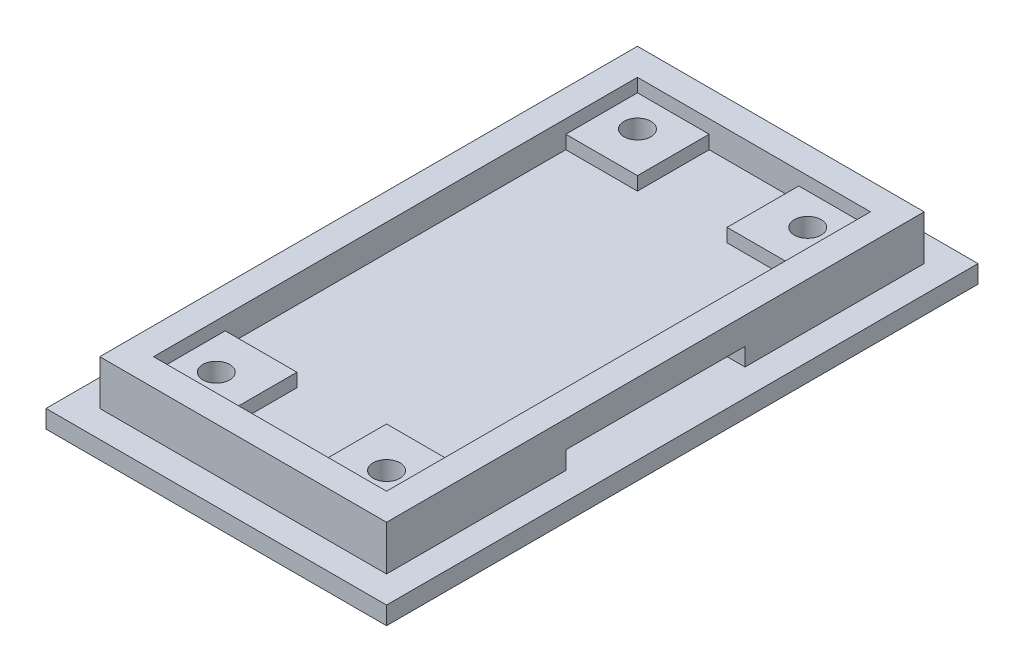
SolidWorks part; units mm, degrees
ref_plane "Front Plane" through (0, 0, 0) normal (0, 0, 1) x (1, 0, 0)
ref_plane "Top Plane" through (0, 0, 0) normal (0, 1, 0) x (1, 0, 0)
ref_plane "Right Plane" through (0, 0, 0) normal (1, 0, 0) x (0, 0, -1)
sketch "Sketch1" plane through (0, 0, 0) normal (0, 1, 0) x (1, 0, 0)
  line L0 (0, -3.85) -> (0, 3.85) construction
  line L1 (-16, 30) -> (16, 30)
  line L2 (-16, 30) -> (-16, -30)
  line L3 (-16, -30) -> (16, -30)
  line L4 (16, 30) -> (16, -30)
  line L5 (-3.85, 0) -> (3.85, 0) construction
  dimension "D1" = 16
  dimension "D2" = 32
  dimension "D3" = 60
  dimension "D4" = 30
extrude "Boss-Extrude1" add sketch "Sketch1" along normal blind 5
sketch "Sketch2" plane through (0, 5, 0) normal (0, 1, 0) x (1, 0, 0)
  line L1 (-13, 27) -> (13, 27)
  line L2 (-13, 27) -> (-13, -27)
  line L3 (-13, -27) -> (13, -27)
  line L4 (13, 27) -> (13, -27)
  line L5 (-16, 30) -> (-16, -30) construction
  line L6 (16, 30) -> (-16, 30) construction
  line L7 (16, -30) -> (16, 30) construction
  line L8 (-16, -30) -> (16, -30) construction
  dimension "D1" = 3
  dimension "D2" = 3
  dimension "D3" = 3
  dimension "D4" = 3
extrude "Cut-Extrude1" cut sketch "Sketch2" against normal blind 3
sketch "Sketch6" plane through (16, 0, -14) normal (-1, 0, 0) x (0, 0, 1)
  line L1 (4, 0) -> (24, 0)
  line L2 (4, 0) -> (4, 2)
  line L3 (4, 2) -> (24, 2)
  line L4 (24, 0) -> (24, 2)
  line L6 (14, -2.75) -> (14, 2.75) construction
  dimension "D1" = 10
  dimension "D2" = 20
  dimension "D3" = 2
extrude "Cut-Extrude4" cut sketch "Sketch6" along normal blind 2
sketch "Sketch7" plane through (0, 0, 0) normal (0, -1, 0) x (1, 0, 0)
  line L0 (-16, -30) -> (-16, 30) construction
  line L1 (-19, 33) -> (19, 33)
  line L2 (-19, 33) -> (-19, -33)
  line L3 (-19, -33) -> (19, -33)
  line L4 (19, 33) -> (19, -33)
  line L5 (-16, 30) -> (16, 30) construction
  line L6 (16, 30) -> (16, 10) construction
  dimension "D1" = 3
  dimension "D2" = 3
  dimension "D3" = 3
extrude "Boss-Extrude3" add sketch "Sketch7" along normal blind 2
sketch "Sketch4" plane through (0, 2, 0) normal (0, 1, 0) x (1, 0, 0)
  line L0 (13, 19) -> (5, 19)
  line L1 (-5, 19) -> (-13, 19)
  line L2 (-5, 19) -> (-5, 27)
  line L3 (-5, 27) -> (-13, 27)
  line L4 (-13, 19) -> (-13, 27)
  line L5 (13, 19) -> (13, 27)
  line L6 (13, 27) -> (5, 27)
  line L7 (5, 19) -> (5, 27)
  line L8 (13, -27) -> (5, -27)
  line L9 (13, -27) -> (13, -19)
  line L10 (13, -19) -> (5, -19)
  line L11 (5, -27) -> (5, -19)
  line L12 (-5, -27) -> (-13, -27)
  line L13 (-5, -27) -> (-5, -19)
  line L14 (-5, -19) -> (-13, -19)
  line L15 (-13, -27) -> (-13, -19)
  dimension "D1" = 8
  dimension "D2" = 8
  dimension "D3" = 2
  dimension "D4" = 2
extrude "Boss-Extrude2" add sketch "Sketch4" along normal blind 1.5
sketch "Sketch3" plane through (0, 3.5, 0) normal (0, 1, 0) x (1, 0, 0)
  line L1 (5, 27) -> (-5, 27) construction
  line L2 (-13, 27) -> (-13, -27) construction
  circle A0 centre (-9.5, 23.5) radius 1.5
  circle A1 centre (9.5, 23.5) radius 1.5
  circle A2 centre (9.5, -23.5) radius 1.5
  circle A3 centre (-9.5, -23.5) radius 1.5
  dimension "D1" = 3.5
  dimension "D2" = 3.5
  dimension "D3" = 2
  dimension "D4" = 2
extrude "Cut-Extrude2" cut sketch "Sketch3" against normal up to surface (5.5 mm away) up to face at (0, -2, 0)
mirror "Mirror1" about plane through (0, 0, 0) normal (1, 0, 0) of "Cut-Extrude4"
